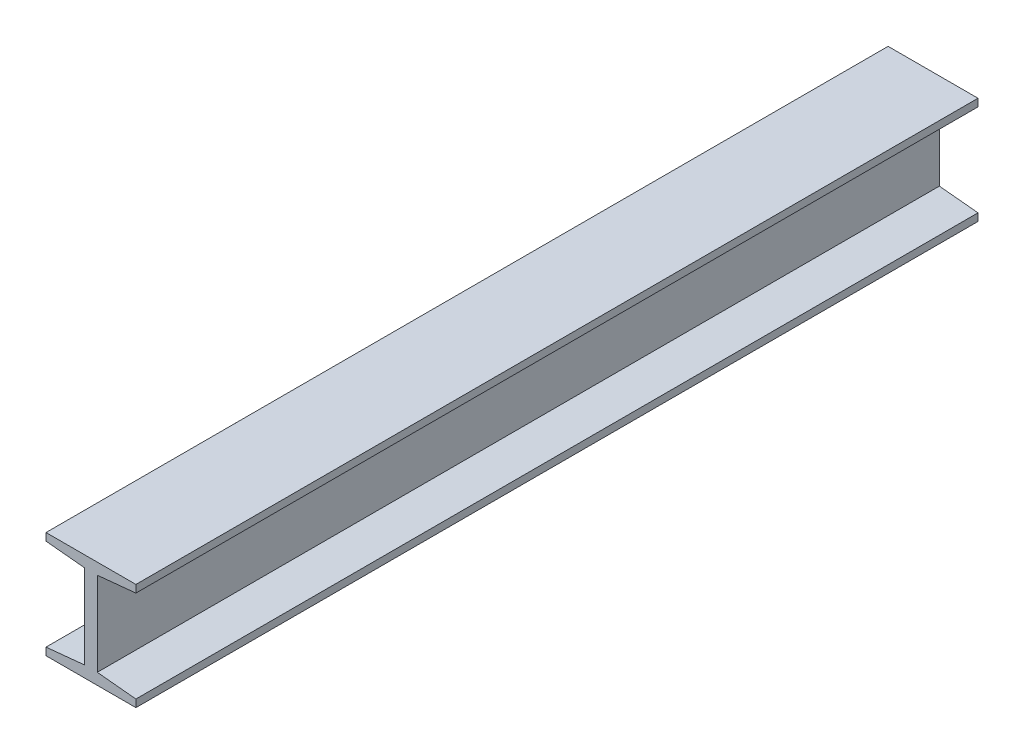
SolidWorks part; units mm, degrees
material "6061-T6 (SS)"
ref_plane "Front Plane" through (0, 0, 0) normal (0, 0, 1) x (1, 0, 0)
ref_plane "Top Plane" through (0, 0, 0) normal (0, 1, 0) x (1, 0, 0)
ref_plane "Right Plane" through (0, 0, 0) normal (1, 0, 0) x (0, 0, -1)
sketch "Sketch1" plane through (0, 0, 0) normal (0, 0, 1) x (1, 0, 0)
  line L0 (-32.03, 38.025) -> (32.03, 38.025)
  line L1 (32.03, 38.025) -> (32.03, 32.68)
  line L2 (32.03, 32.68) -> (4.51, 29.965)
  line L3 (4.51, 29.965) -> (4.51, -29.965)
  line L4 (32.03, -32.68) -> (4.51, -29.965)
  line L5 (32.03, -38.025) -> (32.03, -32.68)
  line L6 (0, -38.025) -> (0, 38.025) construction
  line L7 (-4.51, 0) -> (4.51, 0) construction
  line L8 (-32.03, -38.025) -> (32.03, -38.025)
  line L9 (-32.03, -38.025) -> (-32.03, -32.68)
  line L10 (-32.03, -32.68) -> (-4.51, -29.965)
  line L11 (-4.51, 29.965) -> (-4.51, -29.965)
  line L12 (-32.03, 32.68) -> (-4.51, 29.965)
  line L13 (-32.03, 38.025) -> (-32.03, 32.68)
  point P0 (0, 0)
  point P13 (0, 0)
  dimension "D1" = 4.51
  dimension "D2" = 38.025
  dimension "D3" = 32.68
  dimension "D4" = 29.965
  dimension "D5" = 32.03
extrude "Boss-Extrude1" add sketch "Sketch1" along normal blind 600
equation "\"D1@Sketch1\"=9.02/2"
equation "\"D2@Sketch1\"=76.05/2"
equation "\"D3@Sketch1\"=65.36/2"
equation "\"D4@Sketch1\"=59.93/2"
equation "\"D5@Sketch1\"=(63.95+64.20+64.03)/(2*3)"
